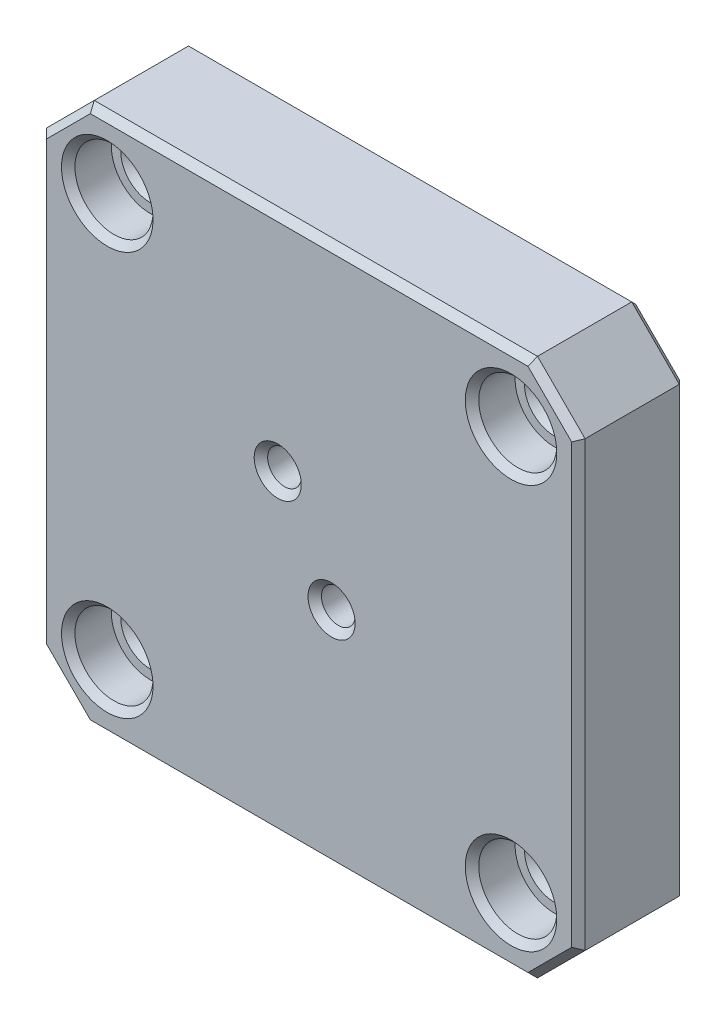
SolidWorks part; units mm, degrees
ref_plane "Top" through (0, 0, 0) normal (0, 0, 1) x (1, 0, 0)
ref_plane "Front" through (0, 0, 0) normal (0, 1, 0) x (1, 0, 0)
ref_plane "Right" through (0, 0, 0) normal (1, 0, 0) x (0, 0, -1)
sketch "Sketch1" plane through (0, 0, 0) normal (0, 0, 1) x (1, 0, 0)
  line L1 (0, 0) -> (40, 0)
  line L2 (0, 0) -> (0, 40)
  line L3 (0, 40) -> (40, 40)
  line L4 (40, 0) -> (40, 40)
  dimension "D1" = 40
  dimension "D2" = 40
extrude "Boss-Extrude1" add sketch "Sketch1" along normal blind 8
sketch "Sketch2" plane through (0, 0, 8) normal (0, 0, 1) x (1, 0, 0)
  line L0 (40, 40) -> (0, 40) construction
  line L1 (5, 35) -> (35, 35) construction
  line L2 (5, 35) -> (5, 5) construction
  line L3 (5, 5) -> (35, 5) construction
  line L4 (35, 35) -> (35, 5) construction
  line L5 (0, 40) -> (0, 0) construction
  circle A0 centre (5, 35) radius 1.7
  circle A1 centre (35, 35) radius 1.7
  circle A2 centre (5, 5) radius 1.7
  circle A3 centre (35, 5) radius 1.7
  dimension "D5" = 3.4
  dimension "D1" = 30
  dimension "D2" = 30
  dimension "D3" = 5
  dimension "D4" = 5
extrude "Cut-Extrude1" cut sketch "Sketch2" against normal through all
sketch "Sketch3" plane through (0, 0, 8) normal (0, 0, 1) x (1, 0, 0)
  line L0 (17.6656, 23.4641) -> (21.6656, 16.5359) construction
  line L1 (40, 0) -> (40, 40) construction
  line L3 (40, 40) -> (0, 40) construction
  line L5 (18.9057, 21.3161) -> (25018.9057, -43279.9541) construction
  line L6 (35, 5) -> (29.9944, 2.11) construction
  circle A0 centre (17.6656, 23.4641) radius 1.25
  circle A1 centre (21.6656, 16.5359) radius 1.25
  point P4 (19.6656, 20)
  dimension "D5" = 2.5
  dimension "D1" = 30
  dimension "D2" = 8
  dimension "D3" = 5.78
  dimension "D4" = 20
extrude "Cut-Extrude2" cut sketch "Sketch3" against normal through all
sketch "Sketch4" plane through (0, 0, 8) normal (0, 0, 1) x (1, 0, 0)
  circle A0 centre (5, 35) radius 2.9
  circle A1 centre (35, 35) radius 2.9
  circle A2 centre (5, 5) radius 2.9
  circle A3 centre (35, 5) radius 2.9
  dimension "D1" = 5.8
extrude "Cut-Extrude3" cut sketch "Sketch4" against normal blind 3.2
chamfer "Chamfer1" distance 3.536 angle 45 4 edges at (0, 40, 4) (40, 40, 4) (40, 0, 4) (0, 0, 4)
chamfer "Chamfer2" distance 0.5 angle 45 32 edges at (1.768, 1.768, 0) (20, 0, 0) (38.232, 1.768, 0) (40, 20, 0) (38.232, 38.232, 0) (20, 40, 0) (1.768, 38.232, 0) (0, 20, 0) (6.7, 35, 0) (36.7, 5, 0) (6.7, 5, 0) (36.7, 35, 0) (22.9156, 16.5359, 0) (18.9156, 23.4641, 0) (38.232, 38.232, 8) (40, 20, 8) (38.232, 1.768, 8) (20, 0, 8) (1.768, 1.768, 8) (0, 20, 8) (1.768, 38.232, 8) (20, 40, 8) (22.9156, 16.5359, 8) (18.9156, 23.4641, 8) (7.9, 35, 8) (37.9, 5, 8) (7.9, 5, 8) (37.9, 35, 8) (36.7, 5, 4.8) (6.7, 5, 4.8) (36.7, 35, 4.8) (6.7, 35, 4.8)
ref_plane "Plane1" through (22.3269, 12.8904, 0) normal (0.866, 0.5, 0) x (0, 0, -1)
ref_plane "Plane2" through (23.4094, 13.5154, 0) normal (0.866, 0.5, 0) x (0, 0, -1)
